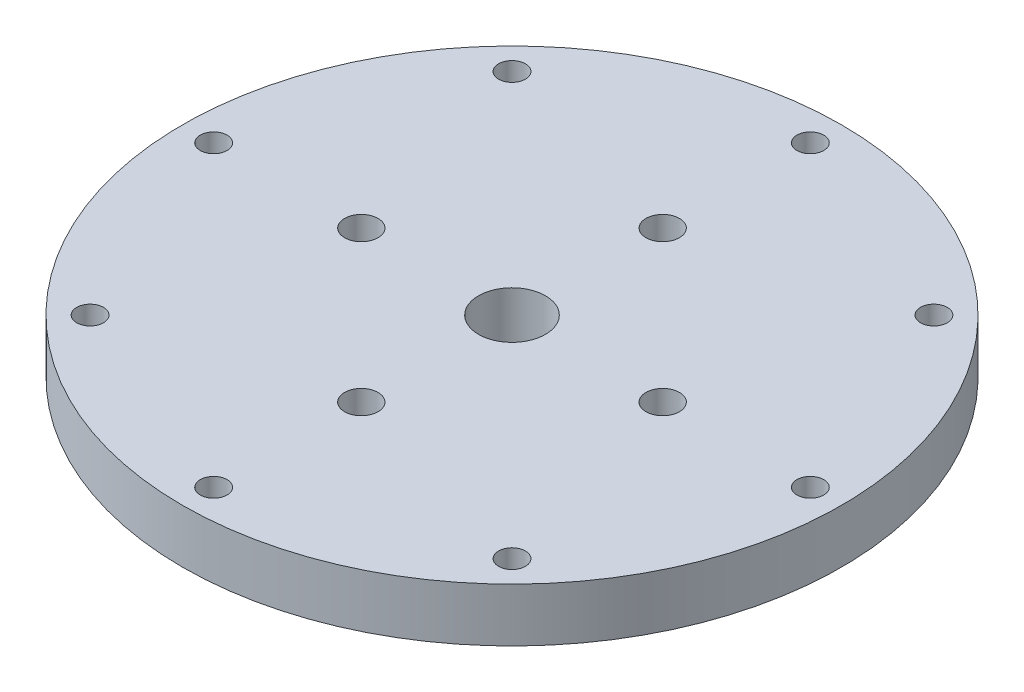
SolidWorks part; units mm, degrees
ref_plane "Front Plane" through (0, 0, 0) normal (0, 0, 1) x (1, 0, 0)
ref_plane "Top Plane" through (0, 0, 0) normal (0, 1, 0) x (1, 0, 0)
ref_plane "Right Plane" through (0, 0, 0) normal (1, 0, 0) x (0, 0, -1)
sketch "Sketch1" plane through (0, 0, 0) normal (0, 1, 0) x (1, 0, 0)
  line L0 (-49.2125, 0) -> (49.2125, 0) construction
  line L1 (0, 49.2125) -> (0, -49.2125) construction
  line L3 (0, 44.5516) -> (-31.5027, 31.5027) construction
  line L4 (-31.5027, 31.5027) -> (-44.5516, 0) construction
  line L5 (-44.5516, 0) -> (-31.5027, -31.5027) construction
  line L6 (-31.5027, -31.5027) -> (0, -44.5516) construction
  line L7 (0, -44.5516) -> (31.5027, -31.5027) construction
  line L8 (31.5027, -31.5027) -> (44.5516, 0) construction
  line L9 (44.5516, 0) -> (31.5027, 31.5027) construction
  line L10 (31.5027, 31.5027) -> (0, 44.5516) construction
  line L17 (0, 22.5044) -> (-22.5044, 0) construction
  line L18 (-22.5044, 0) -> (0, -22.5044) construction
  line L19 (0, -22.5044) -> (22.5044, 0) construction
  line L20 (22.5044, 0) -> (0, 22.5044) construction
  circle A0 centre (0, 0) radius 49.2125
  circle A1 centre (0, 0) radius 5
  circle A2 centre (0, 0) radius 41.1603 construction
  circle A3 centre (-44.5516, 0) radius 2
  circle A4 centre (-31.5027, 31.5027) radius 2
  circle A5 centre (0, 44.5516) radius 2
  circle A6 centre (-31.5027, -31.5027) radius 2
  circle A7 centre (0, -44.5516) radius 2
  circle A8 centre (31.5027, -31.5027) radius 2
  circle A9 centre (44.5516, 0) radius 2
  circle A10 centre (31.5027, 31.5027) radius 2
  circle A11 centre (0, 0) radius 15.913 construction
  circle A12 centre (-22.5044, 0) radius 2.5
  circle A13 centre (0, 22.5044) radius 2.5
  circle A14 centre (22.5044, 0) radius 2.5
  circle A15 centre (0, -22.5044) radius 2.5
  point P4 (0, -49.2125)
  point P5 (0, 0)
  point P6 (0, 49.2125)
  dimension "D1" = 98.425
  dimension "D2" = 10
  dimension "D4" = 4
  dimension "D5" = 4
  dimension "D6" = 4
  dimension "D7" = 4
  dimension "D8" = 4
  dimension "D9" = 4
  dimension "D10" = 4
  dimension "D11" = 4
  dimension "D13" = 5
  dimension "D14" = 5
  dimension "D15" = 5
  dimension "D16" = 5
  dimension "D3" = 44.5516
  dimension "D12" = 22.5044
extrude "Boss-Extrude1" add sketch "Sketch1" along normal blind 8.001
